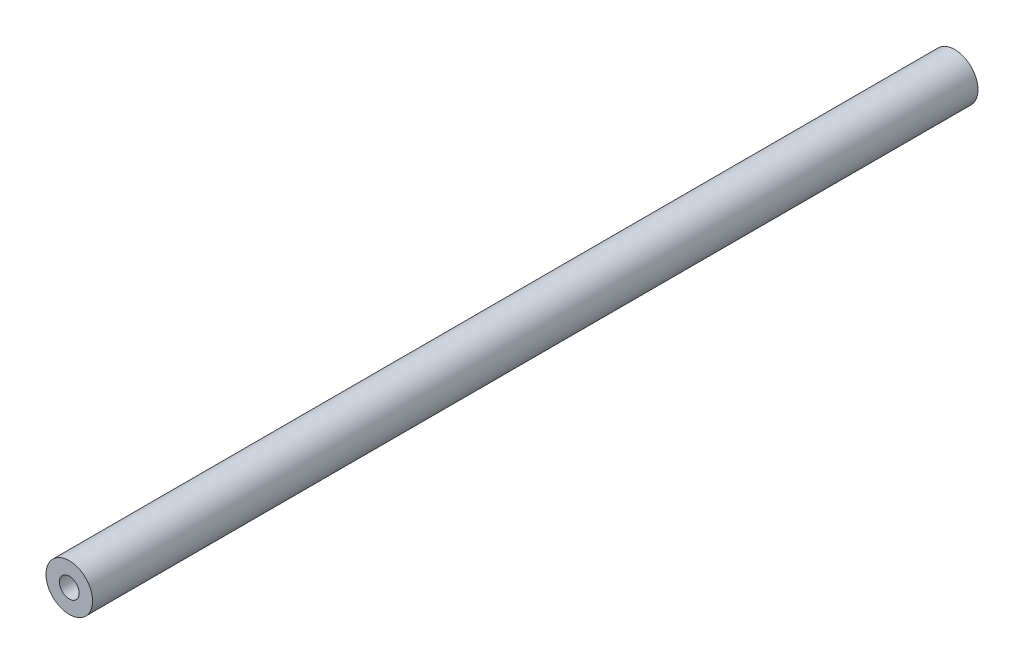
SolidWorks part; units mm, degrees
material "6061-T6 (SS)"
ref_plane "Front Plane" through (0, 0, 0) normal (0, 0, 1) x (1, 0, 0)
ref_plane "Top Plane" through (0, 0, 0) normal (0, 1, 0) x (1, 0, 0)
ref_plane "Right Plane" through (0, 0, 0) normal (1, 0, 0) x (0, 0, -1)
sketch "Sketch1" plane through (0, 0, 0) normal (0, 0, 1) x (1, 0, 0)
  circle A0 centre (0, 0) radius 4.7625
  dimension "D1" = 9.525
extrude "Boss-Extrude1" add sketch "Sketch1" along normal mid plane 180.975
hole_wizard "#10-32 Tapped Hole1" positions "3DSketch1" profile "Sketch2" tap size "#10-32" standard "ANSI Inch"
sketch3d "3DSketch1"
  line L0 (0, 0, 90.4875) -> (0, 0, -90.4875) construction
  point P0 (0, 0, 90.4875)
  point P4 (0, 0, -90.4875)
sketch "Sketch2" plane through (0, 0, 90.4875) normal (1, 0, 0) x (0, -1, 0)
  line L0 (0, 0) -> (0, 13.1513)
  line L1 (0, 13.1513) -> (2.0193, 11.938)
  line L2 (2.0193, 11.938) -> (2.0193, 0)
  line L5 (2.0193, 0) -> (0, 0)
  line L10 (0, 13.1513) -> (-2.0193, 11.938) construction
  line L11 (0, -6.35) -> (0, 107.95) construction
  dimension "Tap Drill Dia." = 4.0386
  dimension "Tap Drill Depth" = 11.938
  dimension "Drill Angle" = 118
cosmetic thread "Hole Thread1"
cosmetic thread "Hole Thread2"
